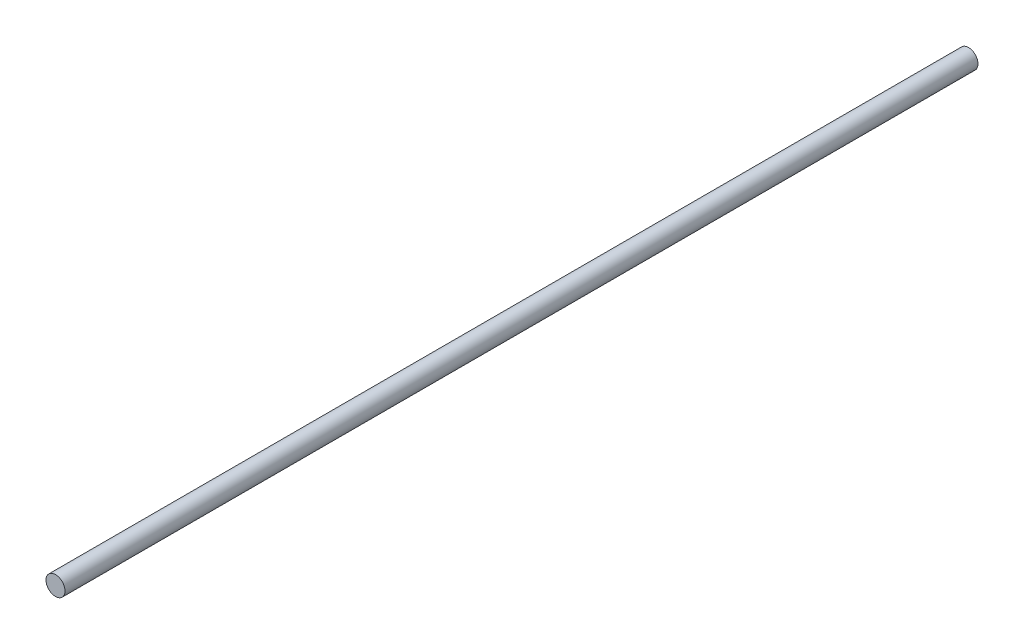
SolidWorks part; units mm, degrees
ref_plane "Plan de face" through (0, 0, 0) normal (0, 0, 1) x (1, 0, 0)
ref_plane "Plan de dessus" through (0, 0, 0) normal (0, 1, 0) x (1, 0, 0)
ref_plane "Plan de droite" through (0, 0, 0) normal (1, 0, 0) x (0, 0, -1)
sketch "Esquisse1" plane through (0, 0, 0) normal (0, 0, 1) x (1, 0, 0)
  circle A0 centre (0, 0) radius 5
  dimension "D1" = 10
extrude "Extrusion1" add sketch "Esquisse1" along normal blind 480
